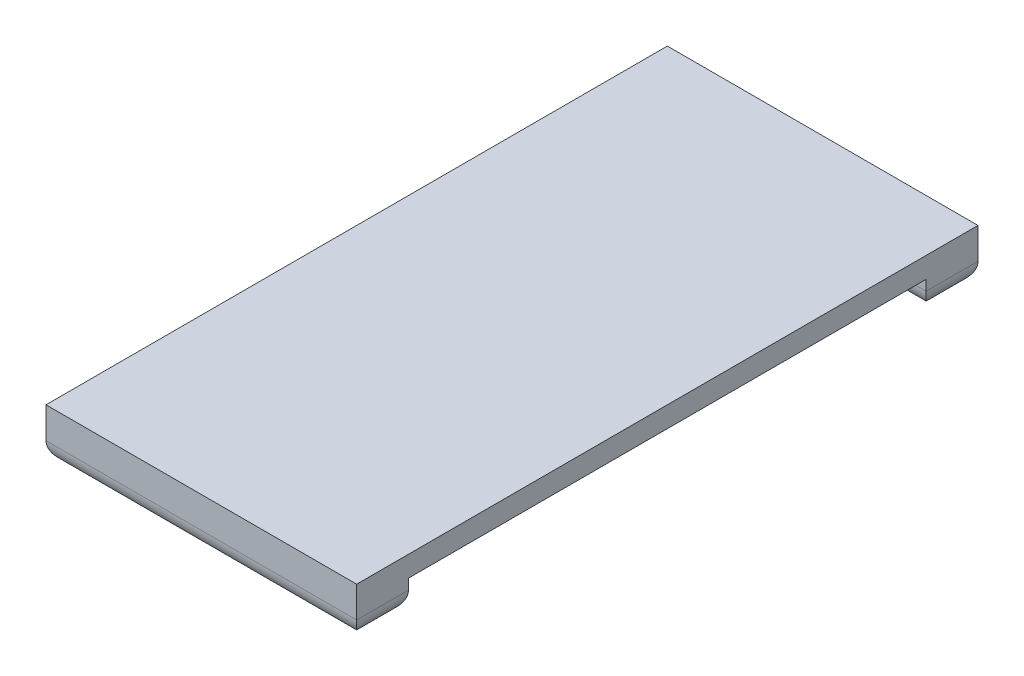
SolidWorks part; units mm, degrees
ref_plane "Front Plane" through (0, 0, 0) normal (0, 0, 1) x (1, 0, 0)
ref_plane "Top Plane" through (0, 0, 0) normal (0, 1, 0) x (1, 0, 0)
ref_plane "Right Plane" through (0, 0, 0) normal (1, 0, 0) x (0, 0, -1)
sketch "Sketch1" plane through (0, 0, 0) normal (0, 1, 0) x (1, 0, 0)
  line L1 (-120.3237, 566.8165) -> (179.6763, 566.8165)
  line L2 (-120.3237, 566.8165) -> (-120.3237, -33.1835)
  line L3 (-120.3237, -33.1835) -> (179.6763, -33.1835)
  line L4 (179.6763, 566.8165) -> (179.6763, -33.1835)
  dimension "D1" = 300
  dimension "D2" = 600
extrude "Boss-Extrude1" add sketch "Sketch1" along normal blind 50
sketch "Sketch2" plane through (0, 0, 0) normal (0, -1, 0) x (-1, 0, 0)
  line L0 (120.3237, 566.8165) -> (120.3237, -33.1835) construction
  line L1 (120.3237, 16.8165) -> (-179.6763, 16.8165)
  line L2 (120.3237, 16.8165) -> (120.3237, 516.8165)
  line L3 (120.3237, 516.8165) -> (-179.6763, 516.8165)
  line L4 (-179.6763, 16.8165) -> (-179.6763, 516.8165)
  line L5 (-179.6763, -33.1835) -> (-179.6763, 566.8165) construction
  line L6 (-179.6763, 566.8165) -> (120.3237, 566.8165) construction
  line L7 (120.3237, -33.1835) -> (-179.6763, -33.1835) construction
  dimension "D1" = 50
  dimension "D2" = 50
extrude "Cut-Extrude1" cut sketch "Sketch2" against normal blind 30
sketch "Sketch3" plane through (0, 0, 0) normal (0, -1, 0) x (-1, 0, 0)
  line L0 (-179.6763, 16.8165) -> (120.3237, 16.8165) construction
  line L1 (-4.6763, 16.8165) -> (-54.6763, 16.8165)
  line L2 (-4.6763, 16.8165) -> (-4.6763, 516.8165)
  line L3 (-4.6763, 516.8165) -> (-54.6763, 516.8165)
  line L4 (-54.6763, 16.8165) -> (-54.6763, 516.8165)
  line L5 (120.3237, 516.8165) -> (-179.6763, 516.8165) construction
  line L7 (120.3237, 16.8165) -> (120.3237, -33.1835) construction
  line L8 (-179.6763, -33.1835) -> (-179.6763, 16.8165) construction
  dimension "D1" = 125
  dimension "D2" = 125
extrude "Boss-Extrude2" add sketch "Sketch3" against normal blind 36
fillet "Fillet1" radius 20 12 edges at (29.6763, 0, -566.8165) (-120.3237, 0, -541.8165) (-57.8237, 0, -516.8165) (4.6763, 0, -266.8165) (-57.8237, 0, -16.8165) (-120.3237, 0, 8.1835) (29.6763, 0, 33.1835) (179.6763, 0, 8.1835) (117.1763, 0, -16.8165) (54.6763, 0, -266.8165) (117.1763, 0, -516.8165) (179.6763, 0, -541.8165)
